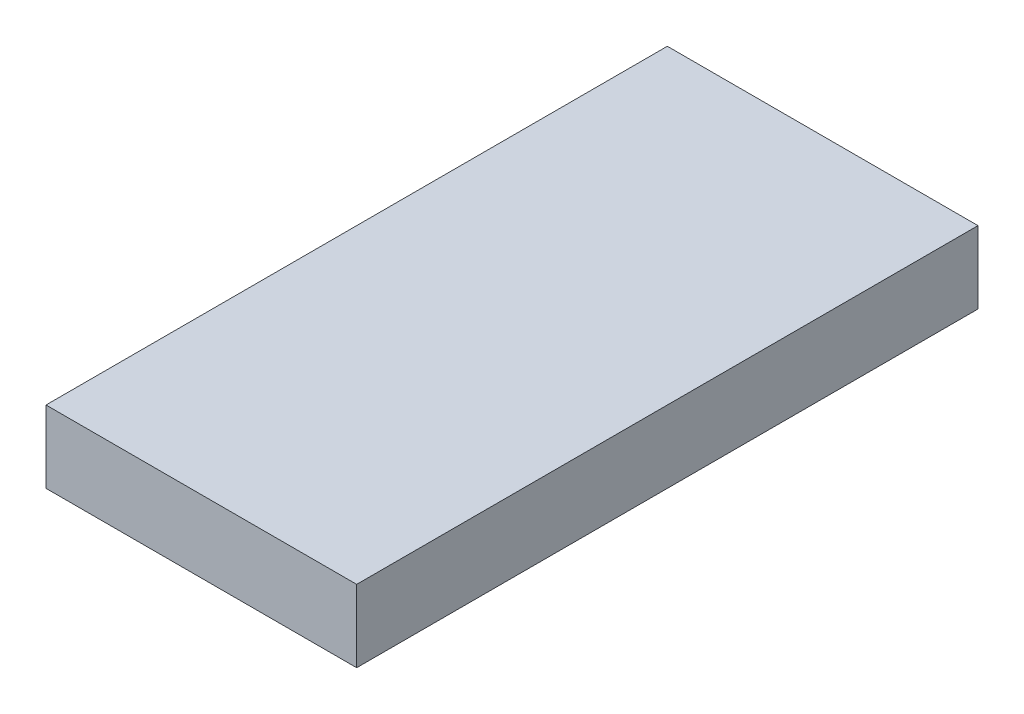
SolidWorks part; units mm, degrees
material "Mahogany"
ref_plane "Front Plane" through (0, 0, 0) normal (0, 0, 1) x (1, 0, 0)
ref_plane "Top Plane" through (0, 0, 0) normal (0, 1, 0) x (1, 0, 0)
ref_plane "Right Plane" through (0, 0, 0) normal (1, 0, 0) x (0, 0, -1)
sketch "Base_Sketch" plane through (0, 0, 0) normal (0, 1, 0) x (1, 0, 0)
  line L0 (-346.6872, 565.3006) -> (-295.8872, 565.3006) construction
  line L1 (-346.6872, 616.1006) -> (-295.8872, 616.1006)
  line L2 (-346.6872, 616.1006) -> (-346.6872, 514.5006)
  line L3 (-346.6872, 514.5006) -> (-295.8872, 514.5006)
  line L4 (-295.8872, 616.1006) -> (-295.8872, 514.5006)
  line L5 (-346.6872, 616.1006) -> (-295.8872, 514.5006) construction
  line L6 (-346.6872, 514.5006) -> (-295.8872, 616.1006) construction
  line L7 (-334.8772, 526.3106) -> (-307.6972, 526.3106) construction
  line L8 (-307.6972, 604.2906) -> (-307.6972, 526.3106) construction
  line L9 (-334.8772, 604.2906) -> (-307.6972, 604.2906) construction
  line L10 (-334.8772, 604.2906) -> (-334.8772, 526.3106) construction
  line L11 (-358.4972, 502.6906) -> (-284.0772, 502.6906) construction
  line L12 (-284.0772, 627.9106) -> (-284.0772, 502.6906) construction
  line L13 (-358.4972, 627.9106) -> (-284.0772, 627.9106) construction
  line L14 (-358.4972, 627.9106) -> (-358.4972, 502.6906) construction
  line L15 (-612.4972, 616.1006) -> (-284.0772, 616.1006) construction
  line L17 (-307.6972, 514.5006) -> (-588.8772, 514.5006) construction
  point P0 (-321.2872, 565.3006)
  point P16 (-321.2872, 616.1006)
  dimension "D1" = 50.8
  dimension "D2" = 11.81
  dimension "D3" = 11.81
extrude "Boss-Extrude1" add sketch "Base_Sketch" along normal blind 11.81
equation "\"Material_Thickness\"= \"Material_Thickness@Petrov.Assembly\""
equation "\"D1@Boss-Extrude1\"=\"Material_Thickness\""
equation "\"Width\"= \"Accent_Width@Petrov.Assembly\""
equation "\"D1@Base_Sketch\"=\"Width\""
equation "\"D2@Base_Sketch\"=\"Material_Thickness\""
equation "\"D3@Base_Sketch\"=\"Material_Thickness\""
